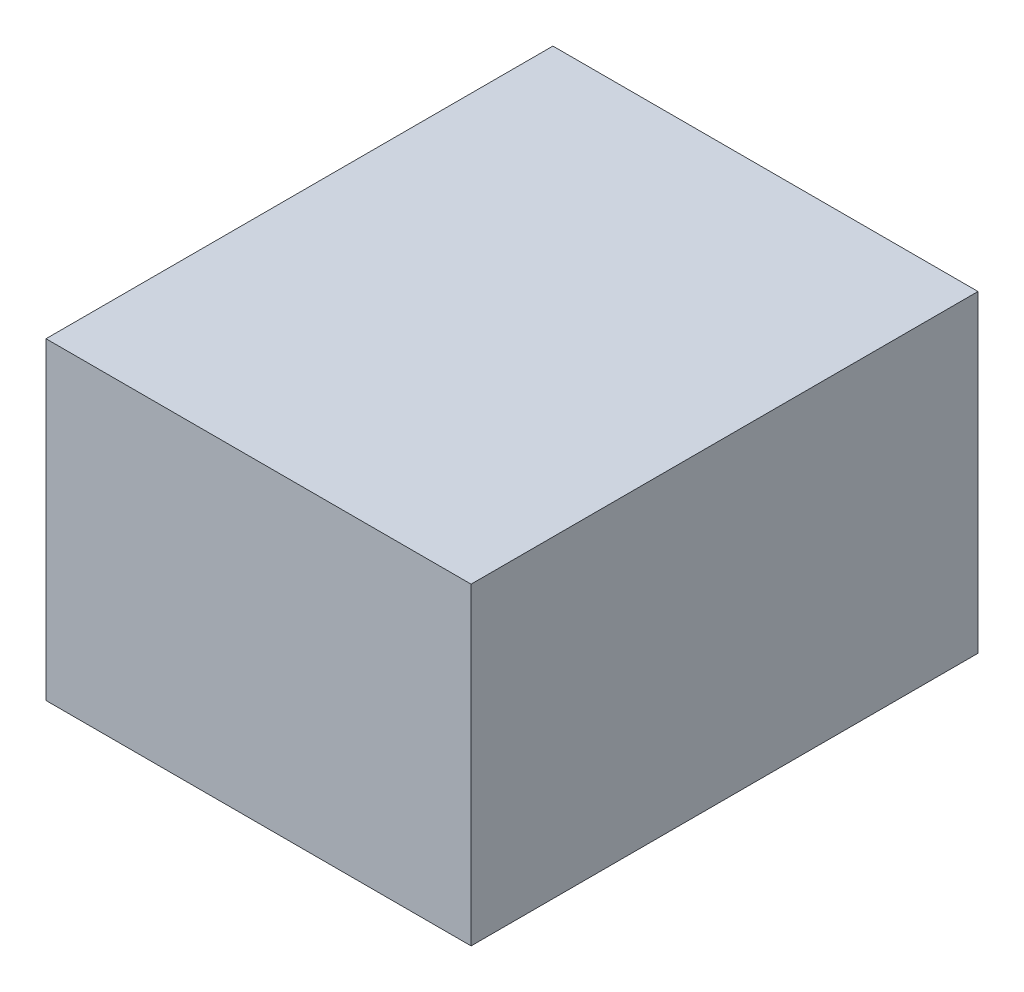
SolidWorks part; units mm, degrees
material "Neutron Star"
ref_plane "Front Plane" through (0, 0, 0) normal (0, 0, 1) x (1, 0, 0)
ref_plane "Top Plane" through (0, 0, 0) normal (0, 1, 0) x (1, 0, 0)
ref_plane "Right Plane" through (0, 0, 0) normal (1, 0, 0) x (0, 0, -1)
sketch "Sketch1" plane through (0, 0, 0) normal (0, 1, 0) x (1, 0, 0)
  line L1 (0, 0) -> (21.3, 0)
  line L2 (0, 0) -> (0, 25.4)
  line L3 (0, 25.4) -> (21.3, 25.4)
  line L4 (21.3, 0) -> (21.3, 25.4)
  dimension "D1" = 21.3
  dimension "D2" = 25.4
extrude "Boss-Extrude1" add sketch "Sketch1" along normal blind 15.7 contours L2 L3 L4 L1
